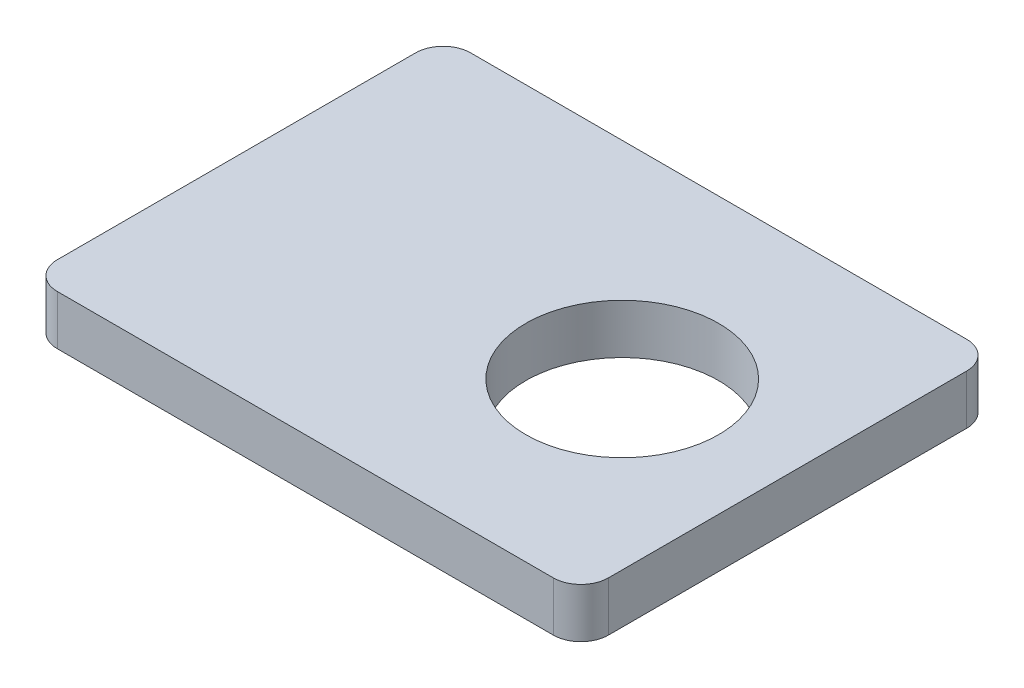
SolidWorks part; units mm, degrees
ref_plane "前视基准面" through (0, 0, 0) normal (0, 0, 1) x (1, 0, 0)
ref_plane "上视基准面" through (0, 0, 0) normal (0, 1, 0) x (1, 0, 0)
ref_plane "右视基准面" through (0, 0, 0) normal (1, 0, 0) x (0, 0, -1)
other "Configuration Table"
sketch "草图1" plane through (0, 0, 0) normal (0, 1, 0) x (1, 0, 0)
  line L1 (-100, -75) -> (100, -75)
  line L2 (-100, -75) -> (-100, 75)
  line L3 (-100, 75) -> (100, 75)
  line L4 (100, -75) -> (100, 75)
  circle A0 centre (40, 0) radius 35
  point P4 (-100, 0)
  point P6 (0, 75)
  dimension "D3" = 70
  dimension "D4" = 75
  dimension "D5" = 60
  dimension "D1" = 150
  dimension "D2" = 200
extrude "凸台-拉伸1" add sketch "草图1" along normal blind 18
fillet "圆角1" radius 10 4 edges at (-100, 9, -75) (100, 9, -75) (100, 9, 75) (-100, 9, 75)
